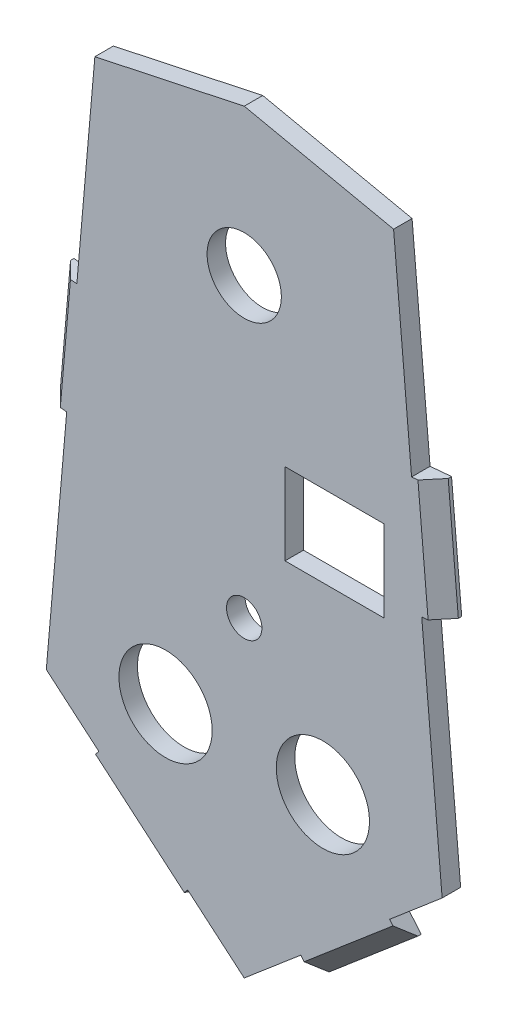
SolidWorks part; units mm, degrees
ref_plane "Front Plane" through (0, 0, 0) normal (0, 0, 1) x (1, 0, 0)
ref_plane "Top Plane" through (0, 0, 0) normal (0, 1, 0) x (1, 0, 0)
ref_plane "Right Plane" through (0, 0, 0) normal (1, 0, 0) x (0, 0, -1)
sketch "Sketch2" plane through (0, 0, 0) normal (0, 0, 1) x (1, 0, 0)
  line L0 (0, 64.8887) -> (0, -64.6913) construction
  line L1 (0, 64.8887) -> (-25.6344, 59.4259)
  line L2 (-25.6344, 59.4259) -> (-33.9676, -35.8235)
  line L3 (-33.9676, -35.8235) -> (0, -64.6913)
  line L4 (0, -64.6913) -> (33.9676, -35.8235)
  line L5 (33.9676, -35.8235) -> (25.6344, 59.4259)
  line L6 (25.6344, 59.4259) -> (0, 64.8887)
  line L7 (-33.9676, -35.8235) -> (33.9676, -35.8235) construction
  line L8 (28.7217, 24.1375) -> (32.4076, 24.46)
  line L9 (32.4076, 24.46) -> (34.1508, 4.5361)
  line L10 (34.1508, 4.5361) -> (30.4648, 4.2136)
  line L11 (30.4648, 4.2136) -> (28.7217, 24.1375)
  line L12 (-28.7217, 24.1375) -> (-32.4076, 24.46)
  line L13 (-32.4076, 24.46) -> (-34.1508, 4.5361)
  line L14 (-34.1508, 4.5361) -> (-30.4648, 4.2136)
  line L15 (-30.4648, 4.2136) -> (-28.7217, 24.1375)
  line L16 (9.6982, -56.4491) -> (11.9648, -59.1161)
  line L17 (11.9648, -59.1161) -> (27.2046, -46.1643)
  line L18 (27.2046, -46.1643) -> (24.938, -43.4974)
  line L19 (24.938, -43.4974) -> (9.6982, -56.4491)
  line L20 (-24.938, -43.4974) -> (-27.2046, -46.1643)
  line L21 (-27.2046, -46.1643) -> (-11.9648, -59.1161)
  line L22 (-11.9648, -59.1161) -> (-9.6982, -56.4491)
  line L23 (-9.6982, -56.4491) -> (-24.938, -43.4974)
  dimension "D1" = 129.58
  dimension "D2" = 26.21
  dimension "D3" = 26.21
  dimension "D4" = 155.94
  dimension "D5" = 107.03
  dimension "D6" = 107.03
  dimension "D7" = 125.36
  dimension "D8" = 3.5
  dimension "D10" = 3.5
  dimension "D11" = 20
  dimension "D12" = 11.85
  dimension "D13" = 11.85
  dimension "D14" = 20
  dimension "D15" = 3.5
  dimension "D16" = 20
  dimension "D17" = 3.7
  dimension "D18" = 20
  dimension "D19" = 3.7
  dimension "D20" = 40.19
  dimension "D21" = 40.19
extrude "Boss-Extrude2" add sketch "Sketch2" along normal blind 3.175 contours L5 L6 L1 L2 L3 L4 | L13 L14 L2 L12 | L10 L9 L8 L5 | L17 L18 L4 L16 | L21 L22 L3 L20
chamfer "Chamfer3" distance 2.6 angle 45 4 edges at (-33.2792, 14.498, 3.175) (33.2792, 14.498, 3.175) (19.5847, -52.6402, 3.175) (-19.5847, -52.6402, 3.175)
sketch "Sketch3" plane through (0, 0, 3.175) normal (0, 0, 1) x (1, 0, 0)
  line L0 (0, 79.6647) -> (0, -96.4859) construction
  line L2 (7, 14.8087) -> (24, 14.8087)
  line L3 (7, 14.8087) -> (7, 0.8087)
  line L4 (7, 0.8087) -> (24, 0.8087)
  line L5 (24, 14.8087) -> (24, 0.8087)
  circle A0 centre (13.5, -30.6913) radius 8
  circle A1 centre (-13.5, -30.6913) radius 8
  circle A3 centre (0, -11.1913) radius 3.0332
  circle A4 centre (0, 39.7345) radius 6.375
  dimension "D9" = 16
  dimension "D10" = 16
  dimension "D11" = 12.75
  dimension "D1" = 27
  dimension "D2" = 13.5
  dimension "D3" = 34
  dimension "D4" = 19.5
  dimension "D5" = 17
  dimension "D6" = 14
  dimension "D7" = 12
  dimension "D8" = 7
extrude "Cut-Extrude1" cut sketch "Sketch3" against normal blind 10
